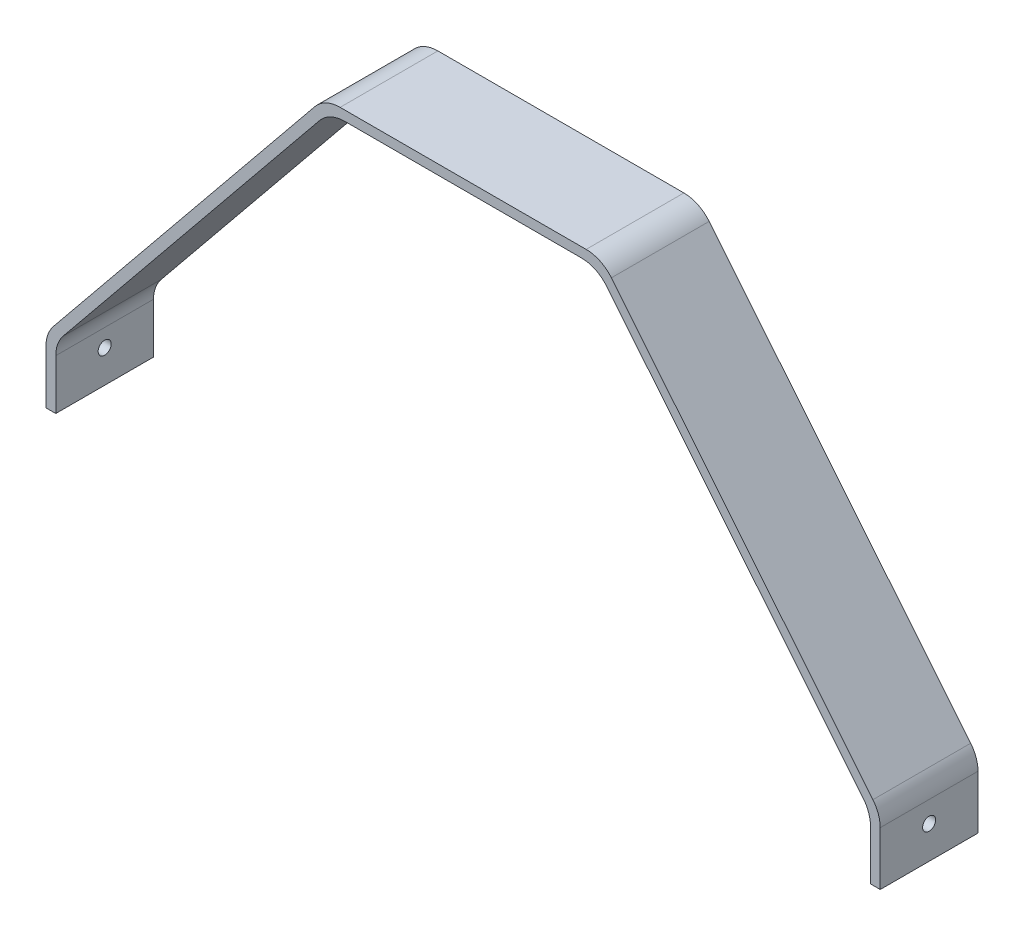
SolidWorks part; units mm, degrees
ref_plane "Front Plane" through (0, 0, 0) normal (0, 0, 1) x (1, 0, 0)
ref_plane "Top Plane" through (0, 0, 0) normal (0, 1, 0) x (1, 0, 0)
ref_plane "Right Plane" through (0, 0, 0) normal (1, 0, 0) x (0, 0, -1)
sketch "Sketch1" plane through (0, 0, 0) normal (0, 0, 1) x (1, 0, 0)
  line L0 (-42.5, 0) -> (42.5, 0)
  line L5 (0, 0) -> (0, -125) construction
  line L6 (42.5, 0) -> (128, -105)
  line L7 (-128, -125) -> (128, -125) construction
  line L8 (128, -125) -> (128, -105)
  line L9 (-128, -125) -> (-128, -105)
  line L10 (-42.5, 0) -> (-128, -105)
  line L11 (-125, -125) -> (-125, -106.0669)
  line L12 (-41.0741, -3) -> (-125, -106.0669)
  line L13 (-41.0741, -3) -> (41.0741, -3)
  line L14 (41.0741, -3) -> (125, -106.0669)
  line L15 (125, -125) -> (125, -106.0669)
  line L16 (-128, -125) -> (-125, -125)
  line L17 (128, -125) -> (125, -125)
  line L18 (125, -125) -> (128, -125)
  line L19 (-128, -125) -> (-125, -125)
  point P3 (0, 0)
  point P13 (0, -125)
  dimension "D1" = 85
  dimension "D2" = 125
  dimension "D3" = 256
  dimension "D4" = 20
  dimension "D5" = 3
extrude "Boss-Extrude1" add sketch "Sketch1" along normal blind 30 contours L17 L8 L6 L0 L10 L9 L16 L11 L12 L13 L14 L15
sketch "Sketch2" plane through (128, 0, 0) normal (1, 0, 0) x (0, 0, -1)
  line L0 (-30, -105) -> (0, -125) construction
  circle A0 centre (-15, -115) radius 2
  dimension "D1" = 4
fillet "Fillet1" radius 10 8 edges at (-125, -106.0669, 15) (-41.0741, -3, 15) (125, -106.0669, 15) (41.0741, -3, 15) (-128, -105, 15) (-42.5, 0, 15) (42.5, 0, 15) (128, -105, 15)
extrude "Cut-Extrude1" cut sketch "Sketch2" against normal through all both
